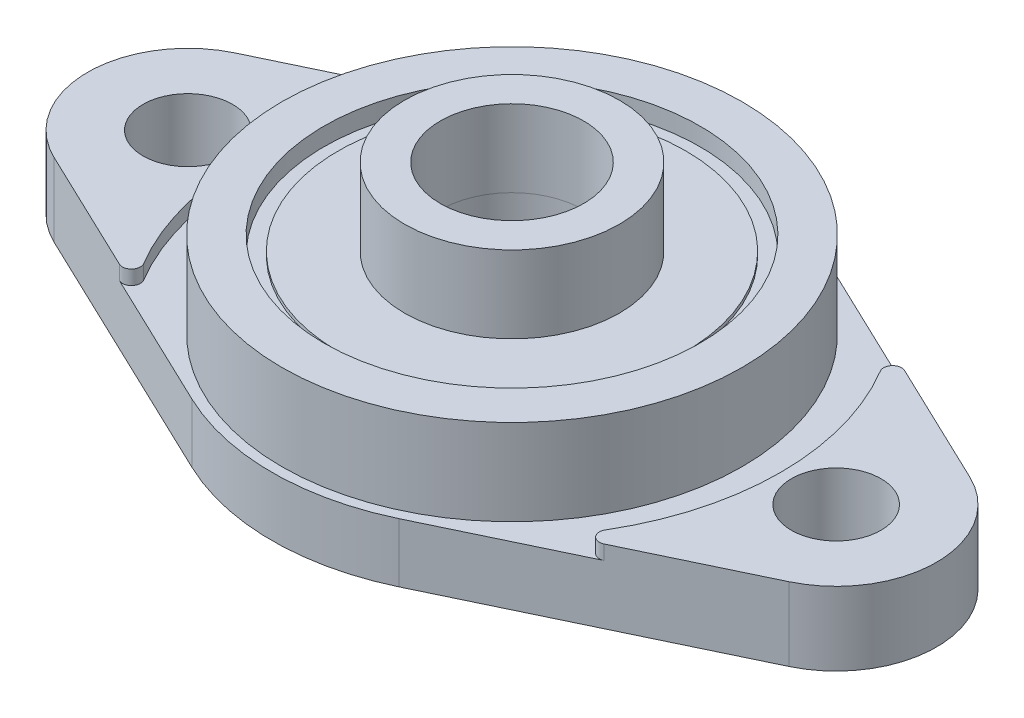
SolidWorks part; units mm, degrees
ref_plane "Front Plane" through (0, 0, 0) normal (0, 0, 1) x (1, 0, 0)
ref_plane "Top Plane" through (0, 0, 0) normal (0, 1, 0) x (1, 0, 0)
ref_plane "Right Plane" through (0, 0, 0) normal (1, 0, 0) x (0, 0, -1)
sketch "Sketch1" plane through (0, 0, 0) normal (0, 1, 0) x (1, 0, 0)
  line L0 (-15.6, 0) -> (15.6, 0)
  line L1 (15.6, 0) -> (20.6, 0)
  line L2 (-15.6, 0) -> (-20.6, 0)
  line L3 (5.7746, 12.0919) -> (20.5133, 5.0533)
  line L4 (-20.5133, 5.0533) -> (-5.7746, 12.0919)
  line L5 (-20.5133, -5.0533) -> (-5.7746, -12.0919)
  line L6 (5.7746, -12.0919) -> (20.5133, -5.0533)
  circle A0 centre (0, 0) radius 13.4
  circle A1 centre (-18.1, 0) radius 2.5
  circle A2 centre (18.1, 0) radius 2.5
  circle A3 centre (-18.1, 0) radius 5.6
  circle A4 centre (18.1, 0) radius 5.6
  circle A5 centre (0, 0) radius 10.5
  point P6 (0, 0)
  dimension "D1" = 26.8
  dimension "D5" = 3.1
  dimension "D6" = 3.1
  dimension "D7" = 21
  dimension "D2" = 31.2
  dimension "D3" = 5
  dimension "D4" = 5
extrude "Boss-Extrude2" add sketch "Sketch1" along normal blind 3.3
sketch "Sketch2" plane through (0, 3.3, 0) normal (0, 1, 0) x (1, 0, 0)
  line L0 (-20.5133, 5.0533) -> (-11.8575, 9.187)
  line L1 (-20.5133, 5.0533) -> (-5.7746, 12.0919) construction
  line L2 (-20.5133, -5.0533) -> (-11.8575, -9.187)
  line L3 (-20.5133, -5.0533) -> (-5.7746, -12.0919) construction
  line L4 (20.5133, -5.0533) -> (11.8575, -9.187)
  line L5 (5.7746, -12.0919) -> (20.5133, -5.0533) construction
  line L6 (20.5133, 5.0533) -> (11.8575, 9.187)
  line L7 (5.7746, 12.0919) -> (20.5133, 5.0533) construction
  circle A0 centre (0, 0) radius 15
  circle A1 centre (-18.1, 0) radius 2.5
  circle A2 centre (18.1, 0) radius 2.5
  circle A3 centre (18.1, 0) radius 5.6
  circle A4 centre (-18.1, 0) radius 5.6
  line M4 (5.7746, -12.0919) -> (20.5133, -5.0533)
  arc M5 (20.5133, -5.0533) -> (20.5133, 5.0533) centre (18.1, 0) ccw
  line M6 (20.5133, 5.0533) -> (5.7746, 12.0919)
  line M8 (-5.7746, 12.0919) -> (-20.5133, 5.0533)
  arc M9 (-20.5133, 5.0533) -> (-20.5133, -5.0533) centre (-18.1, 0) ccw
  line M10 (-20.5133, -5.0533) -> (-5.7746, -12.0919)
  circle M13 centre (-18.1, 0) radius 2.5
  circle M14 centre (18.1, 0) radius 2.5
  dimension "D1" = 30
extrude "Boss-Extrude3" add sketch "Sketch2" along normal blind 0.8 contours A4 A0 M8 | A0 A4 M9 M13 | A4 A0 M10 | A3 A0 M4 | A3 A0 M6 | A3 A0 M5 M14
fillet "Fillet1" radius 0.5 4 edges at (-11.8575, 3.7, -9.187) (-11.8575, 3.7, 9.187) (11.8575, 3.7, 9.187) (11.8575, 3.7, -9.187)
sketch "Sketch3" plane through (0, 3.3, 0) normal (0, 1, 0) x (1, 0, 0)
  circle A0 centre (0, 0) radius 10.5
  circle A1 centre (0, 0) radius 12.85
  dimension "D1" = 25.7
extrude "Boss-Extrude4" add sketch "Sketch3" along normal blind 4.8
sketch "Sketch4" plane through (0, 0, 0) normal (0, -1, 0) x (1, 0, 0)
  circle A0 centre (0, 0) radius 10.5
  circle A1 centre (0, 0) radius 9.7
  dimension "D1" = 0.8
  dimension "D2" = 21
extrude "Boss-Extrude5" add sketch "Sketch4" against normal offset from surface (7.1 mm away) 1 up to face at (0, 8.1, 12.85)
sketch "Sketch6" plane through (0, 0, 0) normal (0, -1, 0) x (1, 0, 0)
  circle A0 centre (0, 0) radius 9.7
extrude "Boss-Extrude7" add sketch "Sketch6" against normal offset from surface (7.3 mm away) 0.8 up to face at (0, 8.1, 12.85)
sketch "Sketch7" plane through (0, 7.3, 0) normal (0, 1, 0) x (1, 0, 0)
  circle A0 centre (0, 0) radius 6
  dimension "D1" = 12
extrude "Cut-Extrude1" cut sketch "Sketch7" against normal blind 26.8 contours A0
sketch "Sketch8" plane through (0, 0, 0) normal (0, -1, 0) x (1, 0, 0)
  circle A0 centre (0, 0) radius 6
extrude "Boss-Extrude8" add sketch "Sketch8" against normal up to surface (7.3 mm away) separate body up to face at (0, 7.3, 6)
sketch "Sketch9" plane through (0, 7.3, 0) normal (0, 1, 0) x (1, 0, 0)
  circle A0 centre (0, 0) radius 6
extrude "Boss-Extrude10" add sketch "Sketch9" along normal blind 4.3 separate body
sketch "Sketch10" plane through (0, 11.6, 0) normal (0, 1, 0) x (1, 0, 0)
  circle A0 centre (0, 0) radius 4
  dimension "D1" = 8
extrude "Cut-Extrude2" cut sketch "Sketch10" against normal blind 25.3
